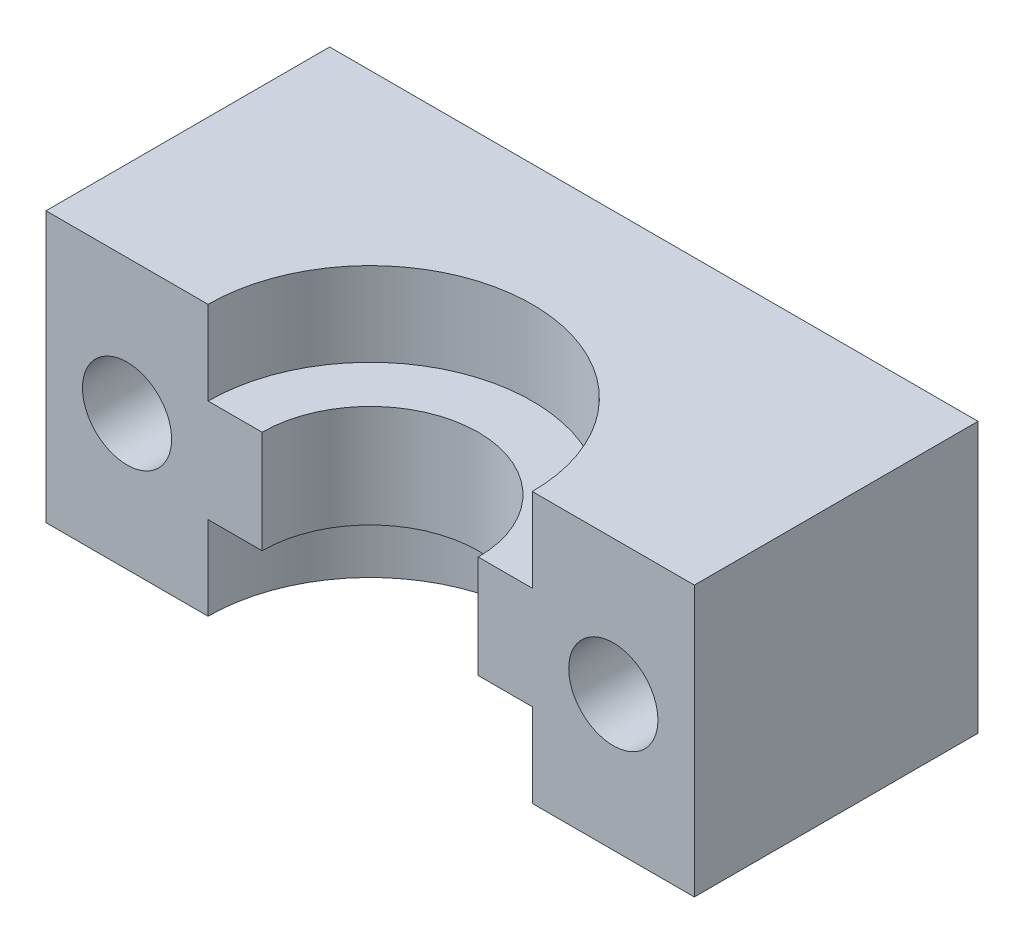
SolidWorks part; units mm, degrees
ref_plane "Alzado" through (0, 0, 0) normal (0, 0, 1) x (1, 0, 0)
ref_plane "Planta" through (0, 0, 0) normal (0, 1, 0) x (1, 0, 0)
ref_plane "Vista lateral" through (0, 0, 0) normal (1, 0, 0) x (0, 0, -1)
sketch "Croquis1" plane through (0, 0, 0) normal (0, 0, 1) x (1, 0, 0)
  line L0 (-9, 0) -> (9, 0) construction
  line L1 (-12, 5) -> (12, 5)
  line L2 (-12, 5) -> (-12, -5)
  line L3 (-12, -5) -> (12, -5)
  line L4 (12, 5) -> (12, -5)
  line L5 (-12, 5) -> (12, -5) construction
  line L6 (-12, -5) -> (12, 5) construction
  circle A0 centre (-9, 0) radius 1.65
  circle A1 centre (9, 0) radius 1.65
  point P0 (0, 0)
  point P13 (0, 0)
  dimension "D3" = 3.3
  dimension "D4" = 18
  dimension "D1" = 24
  dimension "D2" = 10
extrude "Saliente-Extruir1" add sketch "Croquis1" along normal blind 10.5
sketch "Croquis2" plane through (0, 0, 0) normal (1, 0, 0) x (0, 0, -1)
  line L0 (-6.5, 1.9) -> (-6.5, -1.9)
  line L1 (-6.5, 1.9) -> (-4.5, 1.9)
  line L2 (-4.5, 1.9) -> (-4.5, 5)
  line L3 (-4.5, 5) -> (-10.5, 5)
  line L4 (-10.5, -5) -> (-10.5, 5) construction
  line L5 (-10.5, 5) -> (-10.5, -5)
  line L6 (-10.5, -5) -> (-4.5, -5)
  line L7 (-4.5, -5) -> (-4.5, -1.9)
  line L8 (-4.5, -1.9) -> (-6.5, -1.9)
  line L9 (-10.5, 5) -> (0, 5) construction
  line L10 (-10.5, -5) -> (0, -5) construction
  line L11 (-10.5, 5.0628) -> (-10.5, 50005.0628) construction
  point P3 (-6.5, 0)
  dimension "D1" = 4
  dimension "D2" = 6
  dimension "D3" = 3.8
revolve "Cortar-Revolución1" cut sketch "Croquis2" angle 360 about L11
